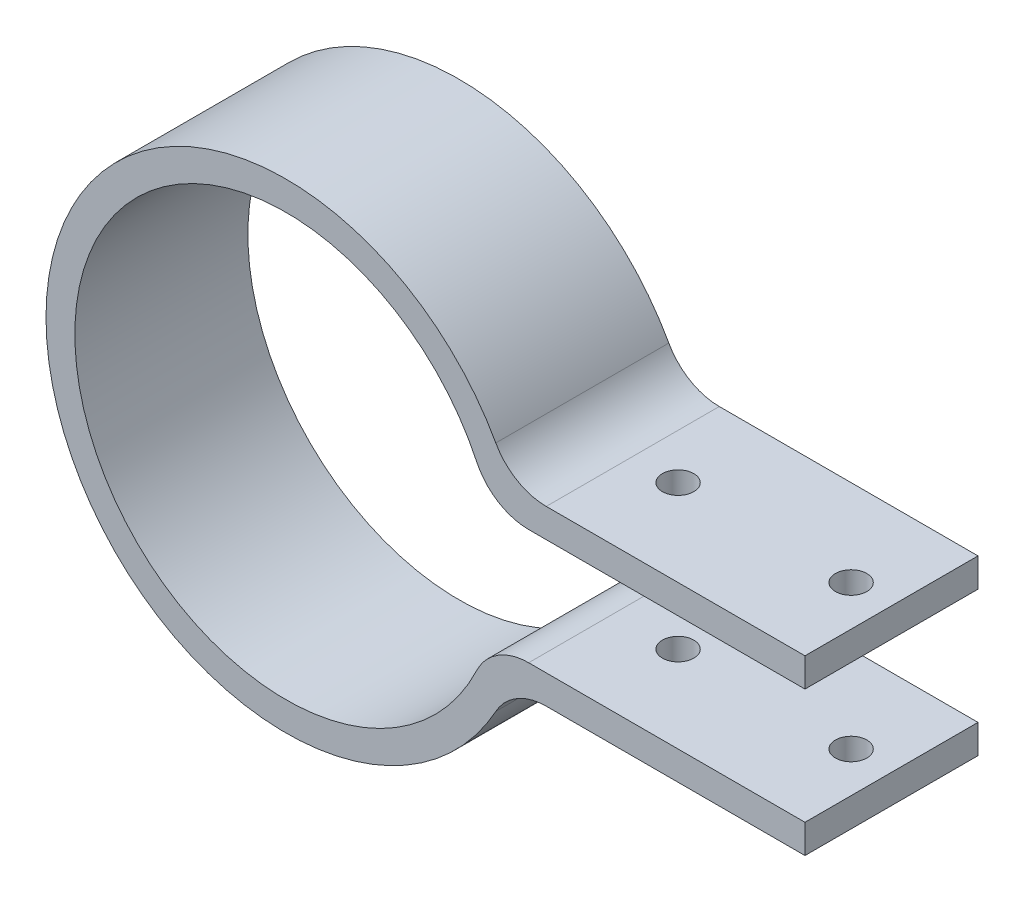
SolidWorks part; units mm, degrees
ref_plane "Front Plane" through (0, 0, 0) normal (0, 0, 1) x (1, 0, 0)
ref_plane "Top Plane" through (0, 0, 0) normal (0, 1, 0) x (1, 0, 0)
ref_plane "Right Plane" through (0, 0, 0) normal (1, 0, 0) x (0, 0, -1)
sketch "Sketch1" plane through (0, 0, 0) normal (0, 0, 1) x (1, 0, 0)
  line L0 (25.4, 0) -> (57.15, 0)
  line L1 (22.3567, 6.35) -> (57.15, 6.35)
  line L2 (57.15, 9.525) -> (57.15, -9.525)
  line L3 (57.15, -6.35) -> (22.3567, -6.35)
  line L4 (57.15, 9.525) -> (24.639, 9.525)
  line L5 (57.15, -9.525) -> (24.639, -9.525)
  circle A0 centre (0, 0) radius 23.241
  circle A1 centre (0, 0) radius 25.4
  circle A2 centre (0, 0) radius 26.416
  dimension "D1" = 50.8
  dimension "D2" = 46.482
  dimension "D4" = 12.7
  dimension "D5" = 31.75
  dimension "D6" = 3.175
  dimension "D7" = 3.175
  dimension "D3" = 3.175
extrude "Boss-Extrude1" add sketch "Sketch1" along normal blind 19.05 contours L1 A1 L3 A0 | A2 L5 L2 L3 | A2 L1 L2 L4 | L1 A2 L3 A1
fillet "Fillet1" radius 6.35 4 edges at (24.639, -9.525, 9.525) (22.3567, -6.35, 9.525) (24.639, 9.525, 9.525) (22.3567, 6.35, 9.525)
sketch "Sketch2" plane through (0, 0, 0) normal (0, 1, 0) x (1, 0, 0)
  line L0 (28.6635, -9.525) -> (57.15, -9.525) construction
  line L1 (28.6635, 0) -> (28.6635, -19.05) construction
  line L2 (57.15, -19.05) -> (57.15, 0) construction
  point P0 (33.655, -9.525)
  point P1 (52.705, -9.525)
  dimension "D1" = 19.05
  dimension "D2" = 4.445
hole_wizard "#29 (0.136) Diameter Hole1" positions "Sketch6" profile "Sketch5" hole size "#29" standard "ANSI Inch" end condition through all
sketch "Sketch6" plane through (0, 9.525, 0) normal (0, 1, 0) x (1, 0, 0)
  point P0 (33.655, -9.525)
  point P3 (52.705, -9.525)
sketch "Sketch5" plane through (33.655, 9.525, 9.525) normal (1, 0, 0) x (0, 0, 1)
  line L0 (0, 0) -> (0, 35.941)
  line L1 (0, 35.941) -> (1.7272, 35.941)
  line L2 (1.7272, 35.941) -> (1.7272, 0)
  line L5 (1.7272, 0) -> (0, 0)
  line L11 (0, -6.35) -> (0, 107.95) construction
  dimension "Thru Hole Dia." = 3.4544
  dimension "Thru Hole Depth" = 35.941
